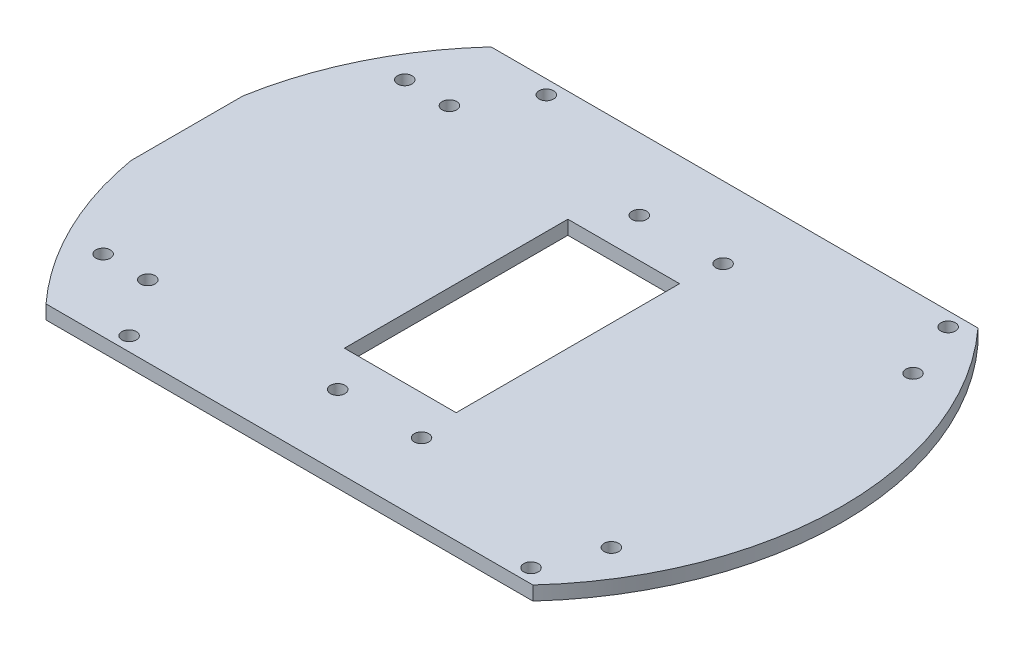
SolidWorks part; units mm, degrees
material "Acrylic (Medium-high impact)"
ref_plane "Front Plane" through (0, 0, 0) normal (0, 0, 1) x (1, 0, 0)
ref_plane "Top Plane" through (0, 0, 0) normal (0, 1, 0) x (1, 0, 0)
ref_plane "Right Plane" through (0, 0, 0) normal (1, 0, 0) x (0, 0, -1)
sketch "Sketch1" plane through (0, 0, 0) normal (0, 1, 0) x (1, 0, 0)
  line L0 (-73.9169, 12.7) -> (-73.9169, -12.7)
  line L2 (-55.356, -50.6035) -> (55.356, -50.6035)
  line L3 (-55.356, 50.6035) -> (55.356, 50.6035)
  line L4 (-48.5169, -34.29) -> (-48.5169, 34.29) construction
  line L5 (-48.5169, 34.29) -> (-5.3369, 34.29) construction
  line L6 (-5.3369, 34.29) -> (-5.3369, -34.29) construction
  line L7 (-5.3369, -34.29) -> (-48.5169, -34.29) construction
  line L8 (-73.9169, 0) -> (-48.5169, 0) construction
  line L9 (0, 50.6035) -> (0, -51.6195) construction
  line L10 (-73.9169, 12.7) -> (-73.9169, -12.7) construction
  line L11 (-12.7, 25.4) -> (12.7, 25.4)
  line L12 (-12.7, 25.4) -> (-12.7, -25.4)
  line L13 (-12.7, -25.4) -> (12.7, -25.4)
  line L14 (12.7, 25.4) -> (12.7, -25.4)
  line L15 (0, 0) -> (0, 25.4) construction
  line L16 (0, 0) -> (-12.7, 0) construction
  line L17 (13.7131, 34.29) -> (13.7131, -34.29) construction
  line L18 (13.7131, -34.29) -> (56.8931, -34.29) construction
  line L19 (56.8931, -34.29) -> (56.8931, 34.29) construction
  line L20 (56.8931, 34.29) -> (13.7131, 34.29) construction
  line L21 (51.7494, 47.4285) -> (51.7494, 50.6035) construction
  line L22 (51.7494, -47.4285) -> (51.7494, -50.6035) construction
  line L23 (-39.6269, -47.4285) -> (-39.6269, -50.6035) construction
  line L24 (-39.6269, 47.4285) -> (-39.6269, 50.6035) construction
  line L25 (51.7494, 47.4285) -> (58.0994, 47.4285) construction
  line L26 (51.7494, -47.4285) -> (58.0994, -47.4285) construction
  arc A0 (-73.9169, -12.7) -> (-55.356, -50.6035) centre (0, 0) ccw
  circle A1 centre (13.7131, 34.29) radius 1.651
  arc A2 (-55.356, 50.6035) -> (-73.9169, 12.7) centre (0, 0) ccw
  arc A3 (55.356, -50.6035) -> (55.356, 50.6035) centre (0, 0) ccw
  circle A4 centre (-58.6769, -34.29) radius 1.651
  circle A5 centre (-58.6769, 34.29) radius 1.651
  circle A6 centre (-39.6269, 47.4285) radius 1.651
  circle A7 centre (51.7494, 47.4285) radius 1.651
  circle A8 centre (-39.6269, -47.4285) radius 1.651
  circle A9 centre (51.7494, -47.4285) radius 1.651
  circle A10 centre (56.8931, 34.29) radius 1.651
  circle A11 centre (-58.6769, 34.29) radius 1.651 construction
  circle A12 centre (-48.5169, 34.29) radius 1.651
  circle A13 centre (-5.3369, 34.29) radius 1.651
  circle A14 centre (-5.3369, -34.29) radius 1.651
  circle A15 centre (-48.5169, -34.29) radius 1.651
  circle A16 centre (13.7131, -34.29) radius 1.651
  circle A17 centre (56.8931, -34.29) radius 1.651
  dimension "D3" = 3.302
  dimension "D1" = 43.18
  dimension "D2" = 68.58
  dimension "D4" = 25.4
  dimension "D5" = 25.4
  dimension "D6" = 50.8
  dimension "D7" = 19.05
  dimension "D8" = 3.175
  dimension "D9" = 6.35
  dimension "D10" = 19.05
extrude "Boss-Extrude1" add sketch "Sketch1" along normal blind 3.175
